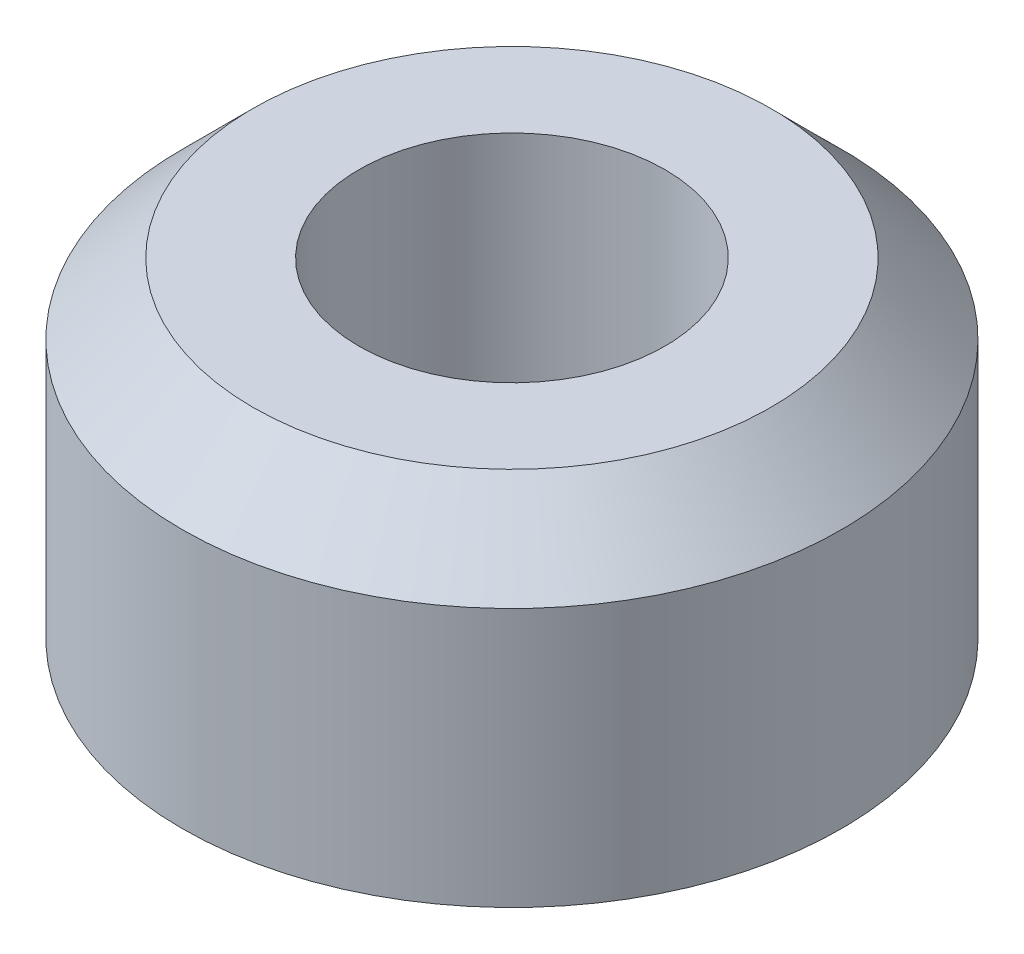
SolidWorks part; units mm, degrees
ref_plane "前视基准面" through (0, 0, 0) normal (0, 0, 1) x (1, 0, 0)
ref_plane "上视基准面" through (0, 0, 0) normal (0, 1, 0) x (1, 0, 0)
ref_plane "右视基准面" through (0, 0, 0) normal (1, 0, 0) x (0, 0, -1)
sketch "草图1" plane through (0, 0, 0) normal (0, 1, 0) x (1, 0, 0)
  circle A0 centre (0, 0) radius 7
  circle A1 centre (0, 0) radius 3.25
  dimension "D1" = 14
  dimension "D2" = 6.5
extrude "凸台-拉伸1" add sketch "草图1" along normal blind 7
chamfer "倒角1" distance 1.5 angle 45 1 edges at (0, 7, 7)
